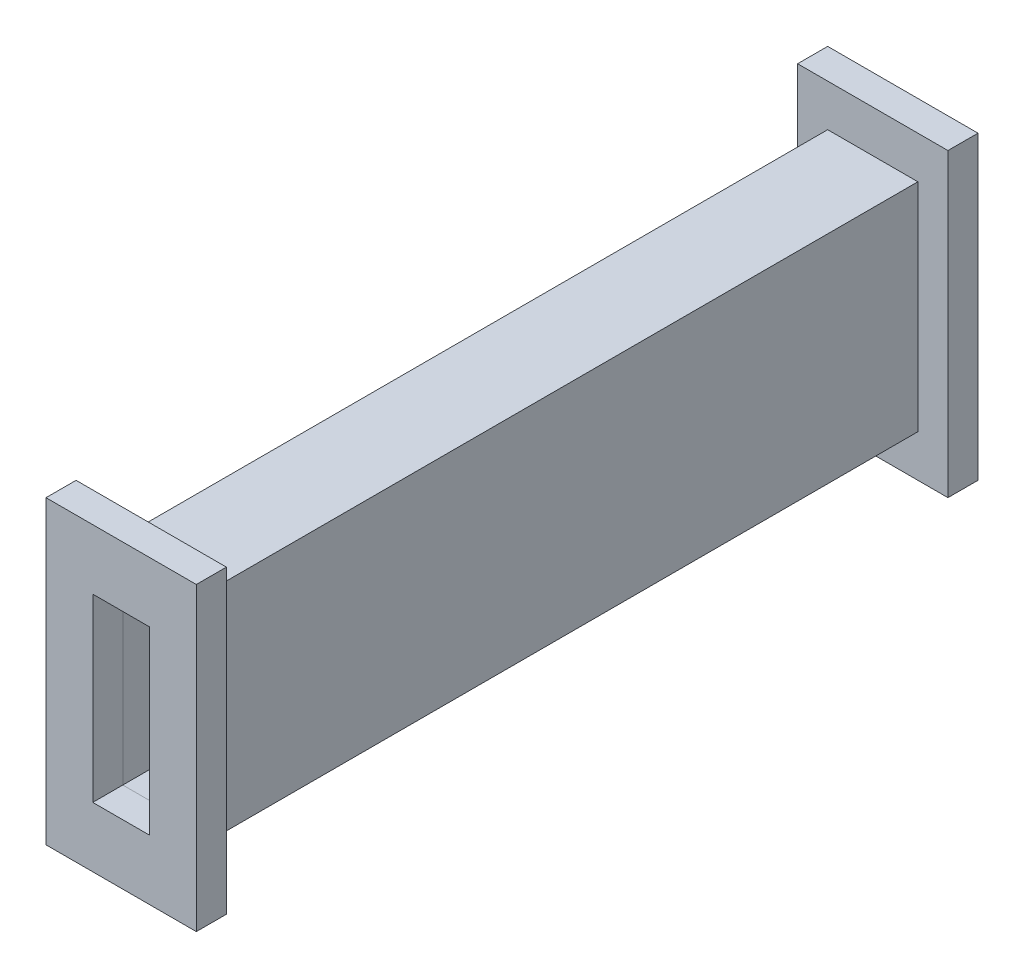
SolidWorks part; units mm, degrees
ref_plane "Front Plane" through (0, 0, 0) normal (0, 0, 1) x (1, 0, 0)
ref_plane "Top Plane" through (0, 0, 0) normal (0, 1, 0) x (1, 0, 0)
ref_plane "Right Plane" through (0, 0, 0) normal (1, 0, 0) x (0, 0, -1)
sketch "Sketch2" plane through (0, 0, 0) normal (0, 0, 1) x (1, 0, 0)
  line L1 (-4.725, 15) -> (4.725, 15)
  line L2 (-4.725, 15) -> (-4.725, -15)
  line L3 (-4.725, -15) -> (4.725, -15)
  line L4 (4.725, 15) -> (4.725, -15)
  line L5 (-4.725, 15) -> (4.725, -15) construction
  line L6 (-4.725, -15) -> (4.725, 15) construction
  line L7 (-7.5, 18) -> (7.5, 18)
  line L8 (-7.5, 18) -> (-7.5, -18)
  line L9 (-7.5, -18) -> (7.5, -18)
  line L10 (7.5, 18) -> (7.5, -18)
  line L11 (-7.5, 18) -> (7.5, -18) construction
  line L12 (-7.5, -18) -> (7.5, 18) construction
  point P0 (0, 0)
  point P6 (0, 0)
  dimension "D1" = 30
  dimension "D2" = 9.45
  dimension "D3" = 15
  dimension "D4" = 36
extrude "Boss-Extrude1" add sketch "Sketch2" along normal mid plane 120
sketch "Sketch3" plane through (0, 0, 60) normal (0, 0, 1) x (1, 0, 0)
  line L1 (4.725, -15) -> (-4.725, -15)
  line L2 (4.725, -15) -> (4.725, 15)
  line L3 (4.725, 15) -> (-4.725, 15)
  line L4 (-4.725, -15) -> (-4.725, 15)
  line L5 (4.725, -15) -> (-4.725, 15) construction
  line L6 (4.725, 15) -> (-4.725, -15) construction
  line L7 (12.5, -25) -> (-12.5, -25)
  line L8 (12.5, -25) -> (12.5, 25)
  line L9 (12.5, 25) -> (-12.5, 25)
  line L10 (-12.5, -25) -> (-12.5, 25)
  line L11 (12.5, -25) -> (-12.5, 25) construction
  line L12 (12.5, 25) -> (-12.5, -25) construction
  point P0 (0, 0)
  point P7 (0, 0)
  point P12 (-7.5, 18)
  point P13 (-4.725, 15)
  dimension "D1" = 50
  dimension "D2" = 25
extrude "Boss-Extrude2" add sketch "Sketch3" along normal blind 5 separate body
mirror "Mirror2" about plane through (0, 0, 0) normal (0, 0, 1) of "Boss-Extrude2"
